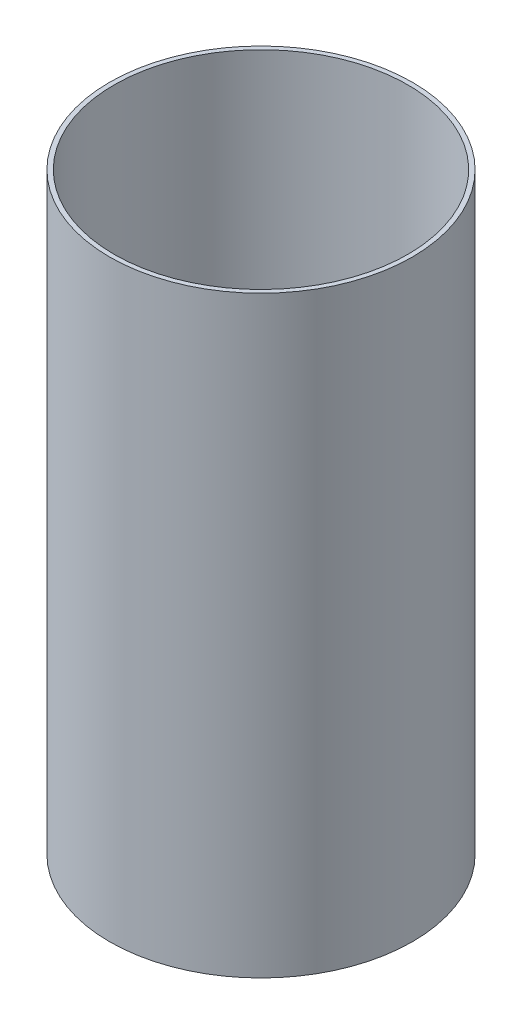
SolidWorks part; units mm, degrees
ref_plane "Front Plane" through (0, 0, 0) normal (1, 0, 0) x (0, 1, 0)
ref_plane "Top Plane" through (0, 0, 0) normal (0, 0, 1) x (0, 1, 0)
ref_plane "Right Plane" through (0, 0, 0) normal (0, 1, 0) x (-1, 0, 0)
sketch "Sketch1" plane through (0, 0, 0) normal (0, 0, 1) x (0, 1, 0)
  line L5 (1778, 51.054) -> (1978, 51.054)
  line L6 (1778, 51.054) -> (1778, 49.53)
  line L7 (1778, 49.53) -> (1978, 49.53)
  line L8 (1978, 51.054) -> (1978, 49.53)
  dimension "D1" = 200
  dimension "D2" = 1778
  dimension "D3" = 49.53
  dimension "D4" = 51.054
ref_axis "Axis1" through (0, 1988, 0) along (0, -1, 0)
revolve "Revolve1" add sketch "Sketch1" angle 360 about axis through (0, 1988, 0) along (0, -1, 0)
